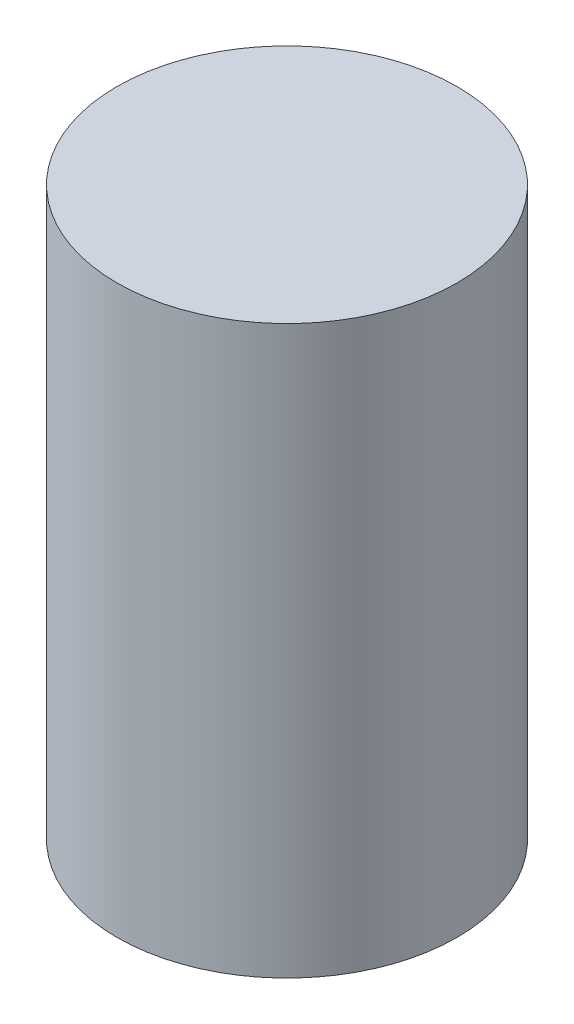
SolidWorks part; units mm, degrees
ref_plane "Front Plane" through (0, 0, 0) normal (0, 0, 1) x (1, 0, 0)
ref_plane "Top Plane" through (0, 0, 0) normal (0, 1, 0) x (1, 0, 0)
ref_plane "Right Plane" through (0, 0, 0) normal (1, 0, 0) x (0, 0, -1)
other "Configuration Table"
sketch "Sketch1" plane through (0, 0, 0) normal (0, 1, 0) x (1, 0, 0)
  circle A0 centre (820, 200) radius 60
extrude "STORE_sog2_kompresor" add sketch "Sketch1" along normal blind 200 from offset 1680 separate body
